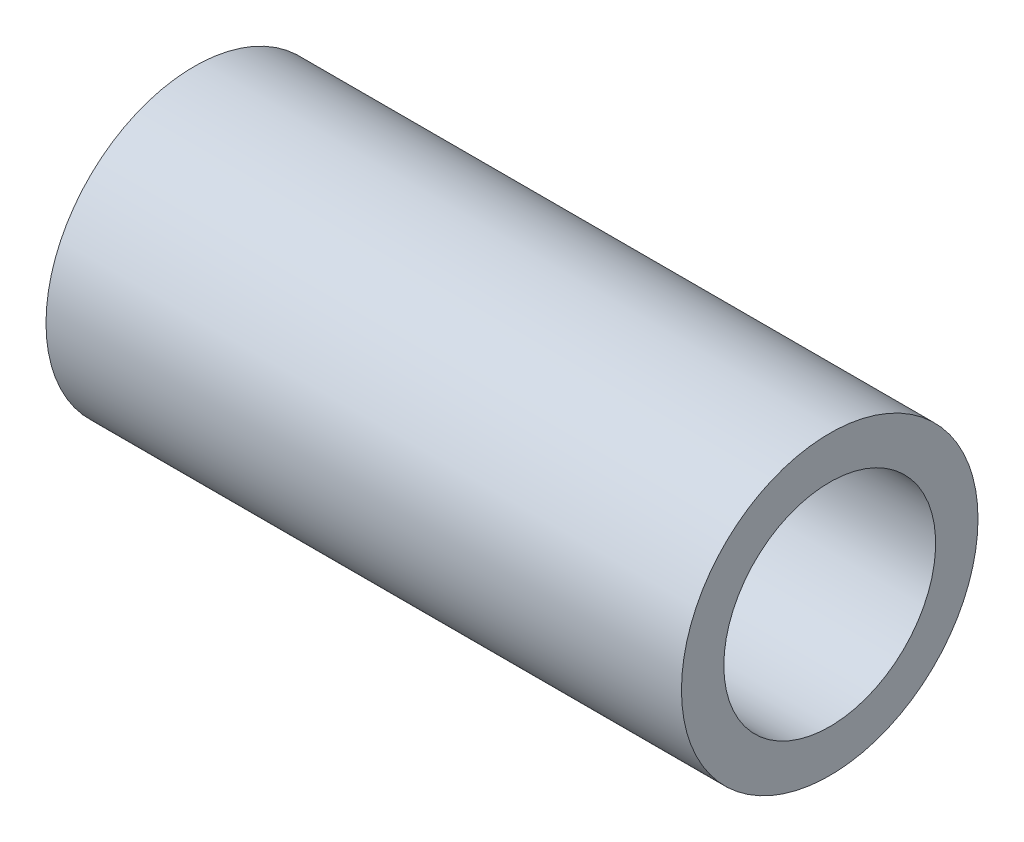
SolidWorks part; units mm, degrees
ref_plane "Ebene vorne" through (0, 0, 0) normal (0, 0, 1) x (1, 0, 0)
ref_plane "Ebene oben" through (0, 0, 0) normal (0, 1, 0) x (1, 0, 0)
ref_plane "Ebene rechts" through (0, 0, 0) normal (1, 0, 0) x (0, 0, -1)
sketch "Skizze1" plane through (0, 0, 0) normal (0, 0, 1) x (1, 0, 0)
  line L0 (0, 0) -> (30, 0) construction
  line L2 (0, 7) -> (30, 7)
  line L3 (0, 7) -> (0, 5)
  line L4 (0, 5) -> (30, 5)
  line L5 (30, 7) -> (30, 5)
  dimension "D1" = 30
  dimension "D2" = 14
  dimension "D3" = 10
revolve "Rotation1" add sketch "Skizze1" angle 360 about L0
